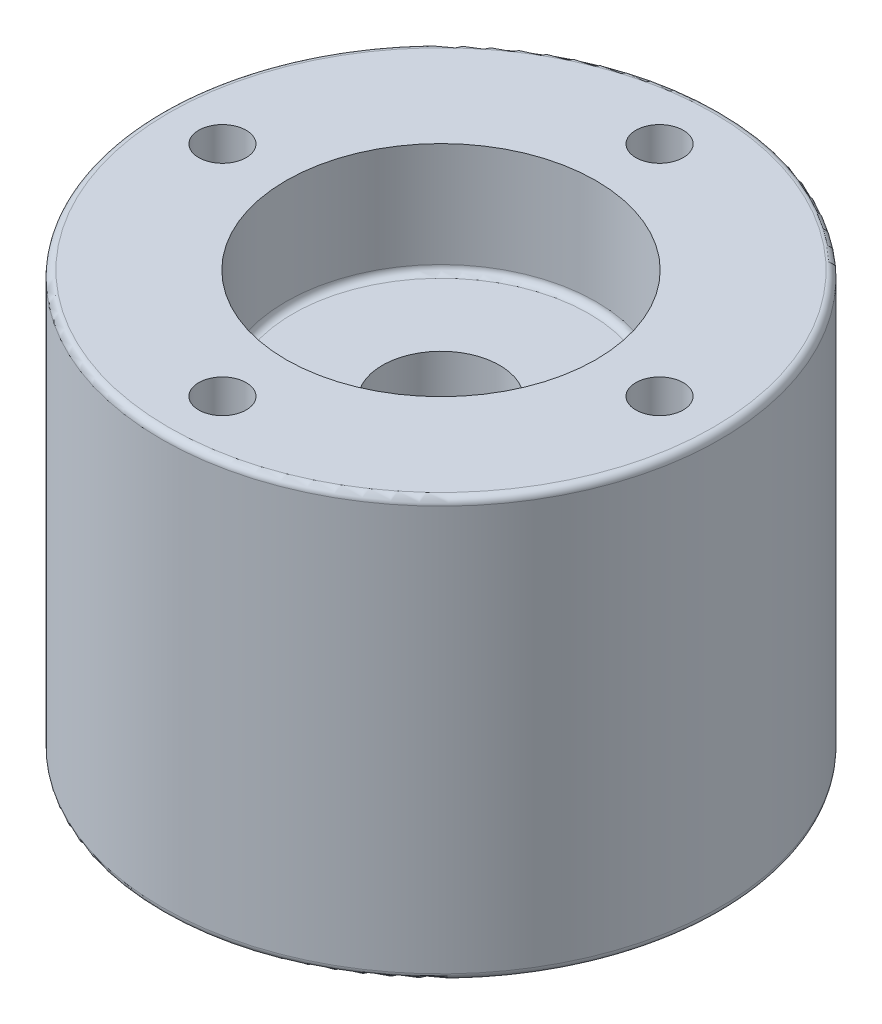
SolidWorks part; units mm, degrees
ref_plane "Front Plane" through (0, 0, 0) normal (0, 0, 1) x (1, 0, 0)
ref_plane "Top Plane" through (0, 0, 0) normal (0, 1, 0) x (1, 0, 0)
ref_plane "Right Plane" through (0, 0, 0) normal (1, 0, 0) x (0, 0, -1)
sketch "Sketch2" plane through (0, 0, 0) normal (0, 1, 0) x (1, 0, 0)
  circle A0 centre (0, 0) radius 20
  dimension "D1" = 40
extrude "Boss-Extrude1" add sketch "Sketch2" along normal blind 30
sketch "Sketch3" plane through (0, 30, 0) normal (0, 1, 0) x (1, 0, 0)
  circle A0 centre (0, 0) radius 11.1
extrude "Cut-Extrude1" cut sketch "Sketch3" against normal blind 8
sketch "Sketch4" plane through (0, 0, 0) normal (0, -1, 0) x (-1, 0, 0)
  circle A0 centre (0, 0) radius 11.1
extrude "Cut-Extrude2" cut sketch "Sketch4" against normal blind 8
sketch "Sketch5" plane through (0, 30, 0) normal (0, 1, 0) x (1, 0, 0)
  circle A1 centre (0, 15.65) radius 1.7
  circle A2 centre (-15.65, 0) radius 1.7
  circle A3 centre (0, -15.65) radius 1.7
  circle A4 centre (15.65, 0) radius 1.7
  point P0 (0, 0)
extrude "Cut-Extrude3" cut sketch "Sketch5" against normal through all
sketch "Sketch6" plane through (0, 22, 0) normal (0, 1, 0) x (1, 0, 0)
  circle A0 centre (0, 0) radius 4.2
extrude "Cut-Extrude4" cut sketch "Sketch6" against normal through all
fillet "Fillet1" radius 0.5 1 edges at (0, 22, 11.1)
fillet "Fillet2" radius 0.5 4 edges at (0, 0, 20) (0, 30, 20) (0, 0, -11.1) (0, 8, -11.1)
